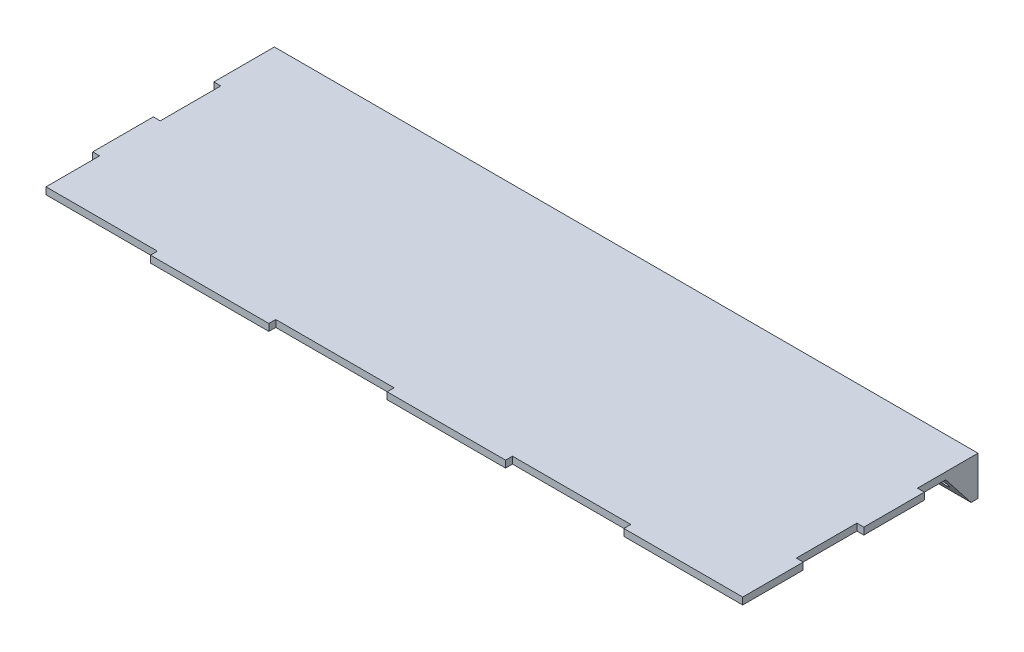
SolidWorks part; units mm, degrees
ref_plane "Спереди" through (0, 0, 0) normal (0, 0, 1) x (1, 0, 0)
ref_plane "Сверху" through (0, 0, 0) normal (0, 1, 0) x (1, 0, 0)
ref_plane "Справа" through (0, 0, 0) normal (1, 0, 0) x (0, 0, -1)
other "Configuration Table"
sketch "Эскиз1" plane through (0, 0, 0) normal (0, 1, 0) x (1, 0, 0)
  line L0 (-121.424, 15.1446) -> (-121.424, 41.3946)
  line L1 (-118.424, -63.6054) -> (186.576, -63.6054)
  line L2 (-121.424, -37.3554) -> (-121.424, -11.1054)
  line L3 (-121.424, 41.3946) -> (183.576, 41.3946)
  line L4 (186.576, -63.6054) -> (186.576, -37.3554)
  line L5 (-118.424, -62.7765) -> (183.576, 97.3135) construction
  line L6 (-121.424, 41.3946) -> (186.576, -63.6054) construction
  line L11 (-121.424, 15.1446) -> (-118.424, 15.1446)
  line L13 (-121.424, -11.1054) -> (-118.424, -11.1054)
  line L14 (-118.424, 15.1446) -> (-118.424, -11.1054)
  line L15 (-121.424, -37.3554) -> (-118.424, -37.3554)
  line L18 (-118.424, -37.3554) -> (-118.424, -63.6054)
  line L21 (186.576, 15.1446) -> (183.576, 15.1446)
  line L22 (183.576, 41.3946) -> (183.576, 15.1446)
  line L23 (186.576, -37.3554) -> (183.576, -37.3554)
  line L25 (186.576, -11.1054) -> (183.576, -11.1054)
  line L26 (183.576, -37.3554) -> (183.576, -11.1054)
  line L27 (186.576, -11.1054) -> (186.576, 15.1446)
  point P0 (0, 0)
  dimension "D1" = 308
  dimension "D2" = 105
  dimension "D3" = 26.25
  dimension "D4" = 26.25
  dimension "D5" = 3
extrude "Бобышка-Вытянуть1" add sketch "Эскиз1" along normal blind 3
sketch "Эскиз2" plane through (0, 3, 0) normal (0, 1, 0) x (1, 0, 0)
  line L0 (-118.424, -63.6054) -> (186.576, -63.6054) construction
  line L1 (-78.924, -43.6054) -> (-38.424, -43.6054)
  line L2 (-78.924, -43.6054) -> (-78.924, -30.3054)
  line L3 (-78.924, -30.3054) -> (-38.424, -30.3054)
  line L4 (-38.424, -43.6054) -> (-38.424, -30.3054)
  line L5 (-121.424, -11.1054) -> (-121.424, -37.3554) construction
  line L6 (-27.124, -43.6054) -> (13.376, -43.6054)
  line L7 (-27.124, -43.6054) -> (-27.124, -30.3054)
  line L8 (-27.124, -30.3054) -> (13.376, -30.3054)
  line L9 (13.376, -43.6054) -> (13.376, -30.3054)
  line L10 (-27.124, -27.0054) -> (13.376, -27.0054)
  line L11 (-27.124, -27.0054) -> (-27.124, -13.7054)
  line L12 (-27.124, -13.7054) -> (13.376, -13.7054)
  line L13 (13.376, -27.0054) -> (13.376, -13.7054)
  line L14 (-78.924, -27.0054) -> (-38.424, -27.0054)
  line L15 (-78.924, -27.0054) -> (-78.924, -13.7054)
  line L16 (-78.924, -13.7054) -> (-38.424, -13.7054)
  line L17 (-38.424, -27.0054) -> (-38.424, -13.7054)
  line L18 (-27.124, -10.4054) -> (13.376, -10.4054)
  line L19 (-27.124, -10.4054) -> (-27.124, 2.8946)
  line L20 (-27.124, 2.8946) -> (13.376, 2.8946)
  line L21 (13.376, -10.4054) -> (13.376, 2.8946)
  line L23 (38.576, -6.1054) -> (58.576, -6.1054)
  line L24 (38.576, -6.1054) -> (38.576, 2.8946)
  line L25 (38.576, 2.8946) -> (58.576, 2.8946)
  line L26 (58.576, -6.1054) -> (58.576, 2.8946)
  line L27 (38.576, -6.1054) -> (58.576, 2.8946) construction
  line L28 (38.576, 2.8946) -> (58.576, -6.1054) construction
  line L30 (98.576, -17.1054) -> (112.576, -17.1054)
  line L31 (98.576, -17.1054) -> (98.576, 2.8946)
  line L32 (98.576, 2.8946) -> (112.576, 2.8946)
  line L33 (112.576, -17.1054) -> (112.576, 2.8946)
  line L34 (98.576, -17.1054) -> (112.576, 2.8946) construction
  line L35 (98.576, 2.8946) -> (112.576, -17.1054) construction
  line L37 (132.576, -29.1054) -> (161.576, -29.1054)
  line L38 (132.576, -29.1054) -> (132.576, 2.8946)
  line L39 (132.576, 2.8946) -> (161.576, 2.8946)
  line L40 (161.576, -29.1054) -> (161.576, 2.8946)
  line L41 (132.576, -29.1054) -> (161.576, 2.8946) construction
  line L42 (132.576, 2.8946) -> (161.576, -29.1054) construction
  point P6 (-78.924, -36.9554)
  point P9 (48.576, -1.6054)
  point P30 (105.576, -7.1054)
  point P35 (147.076, -13.1054)
  dimension "D1" = 40.5
  dimension "D2" = 13.3
  dimension "D3" = 20
  dimension "D4" = 42.5
  dimension "D7" = 3.3
  dimension "D8" = 11.3
  dimension "D10" = 20
  dimension "D11" = 9
  dimension "D12" = 160
  dimension "D13" = 20
  dimension "D14" = 14
  dimension "D15" = 20
  dimension "D16" = 40
  dimension "D17" = 29
  dimension "D18" = 32
  dimension "D19" = 3.3
  dimension "D6" = 2
  dimension "D5" = 2
  dimension "D9" = 2
extrude "Вырез-Вытянуть1" [suppressed] cut sketch "Эскиз2" against normal blind 3
sketch "Эскиз3" plane through (0, 3, 0) normal (0, 1, 0) x (1, 0, 0)
  line L0 (-118.424, -63.6054) -> (186.576, -63.6054) construction
  line L1 (-70.124, -63.6054) -> (-121.424, -63.6054)
  line L2 (-70.124, -63.6054) -> (-70.124, -60.6054)
  line L3 (-70.124, -60.6054) -> (-121.424, -60.6054)
  line L4 (-121.424, -63.6054) -> (-121.424, -60.6054)
  line L5 (-121.424, -11.1054) -> (-121.424, -37.3554) construction
  line L7 (-18.824, -63.6054) -> (32.476, -63.6054)
  line L8 (-18.824, -63.6054) -> (-18.824, -60.6054)
  line L9 (-18.824, -60.6054) -> (32.476, -60.6054)
  line L10 (32.476, -63.6054) -> (32.476, -60.6054)
  line L11 (83.776, -63.6054) -> (135.076, -63.6054)
  line L12 (83.776, -63.6054) -> (83.776, -60.6054)
  line L13 (83.776, -60.6054) -> (135.076, -60.6054)
  line L14 (135.076, -63.6054) -> (135.076, -60.6054)
  dimension "D1" = 51.3
  dimension "D2" = 3
  dimension "D3" = 51.3
  dimension "D4" = 51.3
extrude "Вырез-Вытянуть2" cut sketch "Эскиз3" against normal blind 3
sketch "Эскиз4" plane through (0, 0, 0) normal (0, -1, 0) x (1, 0, 0)
  line L0 (-118.424, -15.1446) -> (-118.424, -41.3946) construction
  line L1 (183.576, -41.3946) -> (-121.424, -41.3946) construction
  line L2 (25.576, -13.3946) -> (29.576, -13.3946)
  line L3 (-118.424, -41.3946) -> (-104.424, -41.3946)
  line L4 (-118.424, -41.3946) -> (-118.424, -27.3946)
  line L5 (-118.424, -27.3946) -> (-104.424, -27.3946)
  line L6 (-104.424, -41.3946) -> (-104.424, -27.3946)
  line L7 (183.576, -41.3946) -> (169.576, -41.3946)
  line L8 (183.576, -41.3946) -> (183.576, -27.3946)
  line L9 (183.576, -27.3946) -> (169.576, -27.3946)
  line L10 (169.576, -41.3946) -> (169.576, -27.3946)
  line L11 (35.576, -13.3946) -> (39.576, -13.3946)
  line L13 (25.576, -41.3946) -> (29.576, -41.3946)
  line L14 (25.576, -41.3946) -> (25.576, -13.3946)
  line L16 (39.576, -41.3946) -> (39.576, -13.3946)
  line L17 (35.576, -13.3946) -> (35.576, -41.3946)
  line L19 (29.576, -13.3946) -> (29.576, -41.3946)
  line L20 (35.576, -41.3946) -> (39.576, -41.3946)
  dimension "D1" = 14
  dimension "D2" = 14
  dimension "D3" = 130
  dimension "D4" = 28
  dimension "D5" = 4
  dimension "D6" = 4
  dimension "D7" = 14
extrude "Бобышка-Вытянуть2" add sketch "Эскиз4" along normal blind 14
sketch "Эскиз6" plane through (39.576, 0, 0) normal (1, 0, 0) x (0, 0, -1)
  line L1 (41.3946, -14) -> (13.3946, -14) construction
  line L4 (13.3946, -14) -> (13.3946, 0)
  line L5 (13.3946, 0) -> (38.3946, -14)
  line L6 (13.3946, -14) -> (38.3946, -14)
  dimension "D1" = 25
extrude "Вырез-Вытянуть3" cut sketch "Эскиз6" against normal blind 14
sketch "Эскиз7" plane through (183.576, 0, 0) normal (1, 0, 0) x (0, 0, -1)
  line L0 (27.3946, -14) -> (27.3946, 0)
  line L1 (27.3946, -14) -> (38.3946, -14)
  line L2 (41.3946, -14) -> (27.3946, -14) construction
  line L3 (38.3946, -14) -> (27.3946, 0)
  dimension "D1" = 11
extrude "Вырез-Вытянуть4" cut sketch "Эскиз7" against normal blind 14
sketch "Эскиз8" plane through (-104.424, 0, 0) normal (1, 0, 0) x (0, 0, -1)
  line L0 (27.3946, -14) -> (27.3946, 0)
  line L1 (41.3946, 0) -> (13.3946, 0) construction
  line L2 (27.3946, 0) -> (38.3946, -14)
  line L3 (38.3946, -14) -> (27.3946, -14)
extrude "Вырез-Вытянуть5" cut sketch "Эскиз8" against normal blind 14
sketch "Эскиз9" plane through (0, 0, -41.3946) normal (0, 0, -1) x (-1, 0, 0)
  line L0 (-169.576, -14) -> (-183.576, -14) construction
  line L1 (-183.576, 3) -> (-183.576, -14) construction
  line L2 (118.424, -14) -> (104.424, -14) construction
  line L3 (104.424, -14) -> (104.424, 0) construction
  circle A0 centre (-176.576, -7) radius 2.5
  circle A1 centre (111.424, -7) radius 2.5
  dimension "D3" = 5
  dimension "D4" = 5
  dimension "D1" = 7
  dimension "D2" = 7
  dimension "D5" = 7
  dimension "D6" = 7
extrude "Вырез-Вытянуть6" cut sketch "Эскиз9" against normal up to vertex
